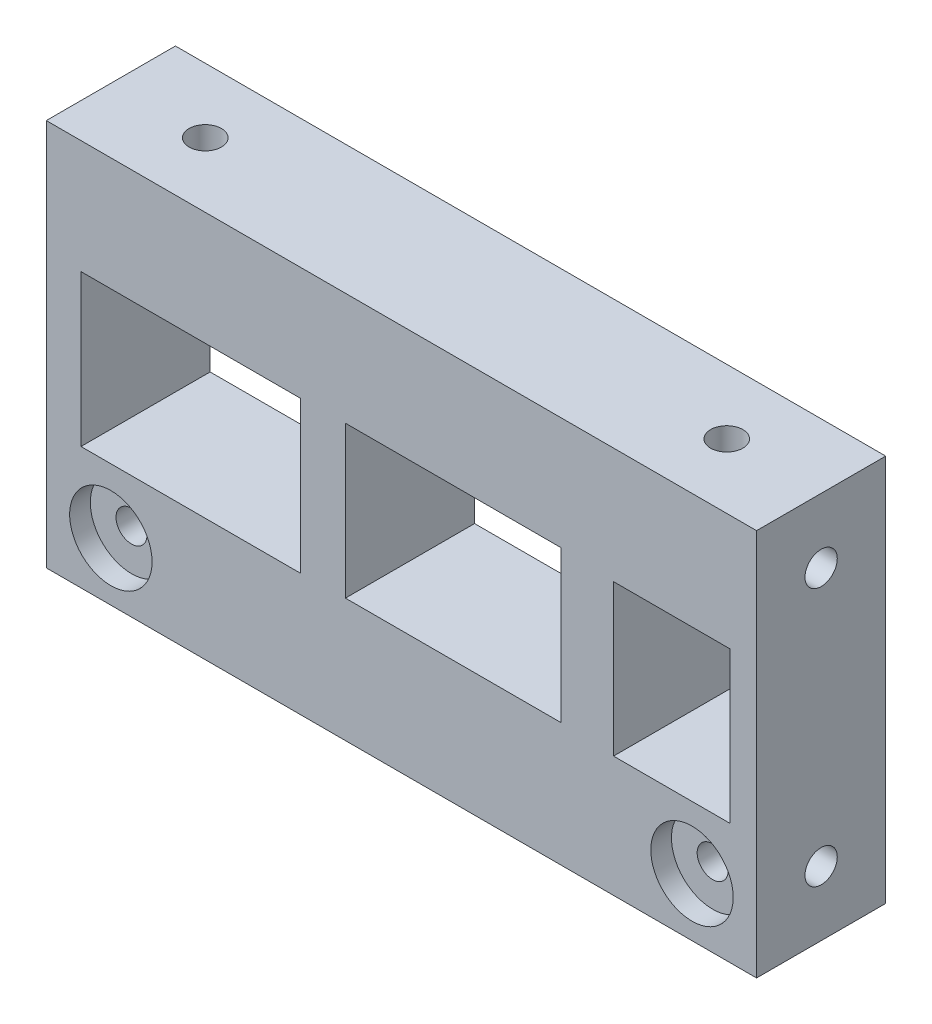
SolidWorks part; units mm, degrees
ref_plane "Front Plane" through (0, 0, 0) normal (0, 0, 1) x (1, 0, 0)
ref_plane "Top Plane" through (0, 0, 0) normal (0, 1, 0) x (1, 0, 0)
ref_plane "Right Plane" through (0, 0, 0) normal (1, 0, 0) x (0, 0, -1)
sketch "Sketch1" plane through (0, 0, 0) normal (0, 0, 1) x (1, 0, 0)
  line L1 (27.5, 15) -> (-27.5, 15)
  line L2 (27.5, 15) -> (27.5, -15)
  line L3 (27.5, -15) -> (-27.5, -15)
  line L4 (-27.5, 15) -> (-27.5, -15)
  line L5 (0, -15) -> (0, 15) construction
  line L6 (27.5, 0) -> (-27.5, 0) construction
  point P0 (0, 0)
  dimension "D1" = 30
  dimension "D2" = 55
extrude "Boss-Extrude1" add sketch "Sketch1" along normal blind 10
sketch "Sketch3" plane through (0, 0, 10) normal (0, 0, 1) x (1, 0, 0)
  line L1 (-24.8128, -5.5149) -> (-7.8207, -5.5149)
  line L2 (-24.8128, -5.5149) -> (-24.8128, 6.2161)
  line L3 (-24.8128, 6.2161) -> (-7.8207, 6.2161)
  line L4 (-7.8207, -5.5149) -> (-7.8207, 6.2161)
  line L5 (-4.3369, 6.2872) -> (12.3709, 6.2872)
  line L6 (-4.3369, 6.2872) -> (-4.3369, -5.4438)
  line L7 (-4.3369, -5.4438) -> (12.3709, -5.4438)
  line L8 (12.3709, 6.2872) -> (12.3709, -5.4438)
  line L9 (16.4234, 6.0432) -> (25.4527, 6.0432)
  line L10 (16.4234, 6.0432) -> (16.4234, -5.6571)
  line L11 (16.4234, -5.6571) -> (25.4527, -5.6571)
  line L12 (25.4527, 6.0432) -> (25.4527, -5.6571)
extrude "Cut-Extrude1" cut sketch "Sketch3" against normal through all
sketch "Sketch4" plane through (0, 0, 10) normal (0, 0, 1) x (1, 0, 0)
  line L12 (-22.5, 10.5) -> (-22.5, -10.5)
  line L13 (-22.5, -10.5) -> (22.5, -10.5)
  line L14 (22.5, -10.5) -> (22.5, 10.5)
  line L15 (22.5, 10.5) -> (-22.5, 10.5)
  line L28 (-27.5, 15) -> (-27.5, -15) construction
  line L29 (27.5, -15) -> (27.5, 15) construction
  line L30 (-27.5, -15) -> (27.5, -15) construction
  point P1 (-22.5, -10.5)
  point P4 (22.5, -10.5)
  dimension "D1" = 5
  dimension "D2" = 5
  dimension "D3" = 4.5
hole_wizard "CBORE for M2 Hex Head Machine Screw2" positions "Sketch4" profile "Sketch7" counterbore size "M2" standard "ANSI Metric" end condition through all
sketch "Sketch7" plane through (-22.5, -10.5, 10) normal (1, 0, 0) x (0, -1, 0)
  line L0 (0, 0) -> (0, 10)
  line L1 (0, 10) -> (1.2, 10)
  line L3 (1.2, 10) -> (1.2, 1.6)
  line L4 (1.2, 1.6) -> (3.19, 1.6)
  line L5 (3.19, 1.6) -> (3.19, 0)
  line L7 (3.19, 0) -> (0, 0)
  line L11 (0, -6.35) -> (0, 107.95) construction
  dimension "Thru Hole Dia." = 2.4
  dimension "Thru Hole Depth" = 10
  dimension "C'Bore Dia." = 6.38
  dimension "C'Bore Depth" = 1.6
sketch "Sketch8" plane through (0, 15, 0) normal (0, 1, 0) x (1, 0, 0)
  line L1 (0, 0) -> (0, 11.02) construction
  line L2 (27.5, -5) -> (-27.5, -5)
  line L3 (27.5, -5) -> (-27.5, -5)
  point P0 (-20.1915, -5)
  point P2 (20.1915, -5)
  dimension "D1" = 5
hole_wizard "M3x0.5 Tapped Hole3" positions "Sketch8" profile "Sketch9" tap size "M3x0.5" standard "ANSI Metric"
cosmetic thread "Hole Thread21" parameters "D1"=25, "D2"=3
cosmetic thread "Hole Thread22" parameters "D1"=25, "D2"=3
sketch "Sketch9" plane through (-20.1915, 15, 5) normal (1, 0, 0) x (0, 0, 1)
  line L0 (0, 0) -> (0, 3.7511)
  line L1 (0, 3.7511) -> (1.25, 3)
  line L2 (1.25, 3) -> (1.25, 0)
  line L5 (1.25, 0) -> (0, 0)
  line L10 (0, 3.7511) -> (-1.25, 3) construction
  line L11 (0, -6.35) -> (0, 107.95) construction
  dimension "Tap Drill Dia." = 2.5
  dimension "Tap Drill Depth" = 3
  dimension "Drill Angle" = 118
sketch "Sketch10" plane through (-27.5, 0, 0) normal (-1, 0, 0) x (0, 0, 1)
  line L1 (5, -15) -> (5, -10) construction
  line L2 (5, 15) -> (5, -15)
  line L3 (5, 15) -> (5, -10) construction
  point P6 (5, -10)
  dimension "D2" = 5
  dimension "D1" = 5
hole_wizard "M3x0.5 Tapped Hole2" positions "Sketch10" profile "Sketch12" tap size "M3x0.5" standard "ANSI Metric"
sketch "Sketch12" plane through (-27.5, -10, 5) normal (0, 1, 0) x (0, 0, 1)
  line L0 (0, 0) -> (0, 3.7511)
  line L1 (0, 3.7511) -> (1.25, 3)
  line L2 (1.25, 3) -> (1.25, 0)
  line L5 (1.25, 0) -> (0, 0)
  line L10 (0, 3.7511) -> (-1.25, 3) construction
  line L11 (0, -6.35) -> (0, 107.95) construction
  dimension "Tap Drill Dia." = 2.5
  dimension "Tap Drill Depth" = 3
  dimension "Drill Angle" = 118
cosmetic thread "Hole Thread42" parameters "D1"=2.55, "D2"=3
sketch "Sketch13" plane through (27.5, 0, 0) normal (1, 0, 0) x (0, 0, -1)
  line L1 (-5, -15) -> (-5, -10)
  line L2 (-5, -15) -> (-5, 15)
  line L3 (-5, -15) -> (-5, 10) construction
  point P9 (-5, -10)
  dimension "D2" = 5
  dimension "D1" = 5
hole_wizard "M3x0.5 Tapped Hole1" positions "Sketch13" profile "Sketch16" tap size "M3x0.5" standard "ANSI Metric"
sketch "Sketch16" plane through (27.5, -10, 5) normal (0, 1, 0) x (0, 0, -1)
  line L0 (0, 0) -> (0, 3.7511)
  line L1 (0, 3.7511) -> (1.25, 3)
  line L2 (1.25, 3) -> (1.25, 0)
  line L5 (1.25, 0) -> (0, 0)
  line L10 (0, 3.7511) -> (-1.25, 3) construction
  line L11 (0, -6.35) -> (0, 107.95) construction
  dimension "Tap Drill Dia." = 2.5
  dimension "Tap Drill Depth" = 3
  dimension "Drill Angle" = 118
cosmetic thread "Hole Thread41" parameters "D1"=2.55, "D2"=3
sketch "Sketch17" plane through (27.5, 0, 0) normal (1, 0, 0) x (0, 0, -1)
  line L0 (-5, 15) -> (-5, -15) construction
  line L1 (-10, 15) -> (0, 15) construction
  line L2 (-10, -15) -> (0, -15) construction
  line L3 (-2.5, 0) -> (-29.0037, 0) construction
ref_plane "Plane1" through (0, 0, 0) normal (0, 1, 0) x (0, 0, 1)
mirror "Mirror1" about plane through (0, 0, 0) normal (0, 1, 0) of "M3x0.5 Tapped Hole1"
cosmetic thread "Hole Thread43" parameters "D1"=2.55, "D2"=3
mirror "Mirror2" about plane through (0, 0, 0) normal (0, 1, 0) of "M3x0.5 Tapped Hole2"
cosmetic thread "Hole Thread44" parameters "D1"=2.55, "D2"=3
